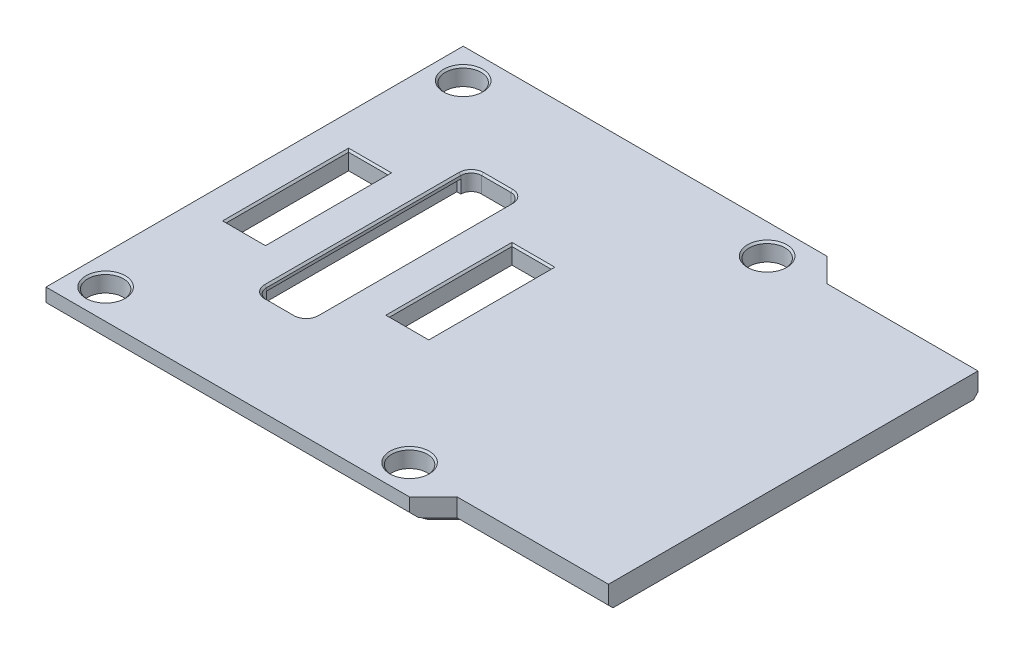
SolidWorks part; units mm, degrees
ref_plane "Front Plane" through (0, 0, 0) normal (0, 0, 1) x (1, 0, 0)
ref_plane "Top Plane" through (0, 0, 0) normal (0, 1, 0) x (1, 0, 0)
ref_plane "Right Plane" through (0, 0, 0) normal (1, 0, 0) x (0, 0, -1)
sketch "Sketch3" plane through (0, 0, 0) normal (0, 1, 0) x (1, 0, 0)
  line L0 (13.7, 0) -> (0, 0) construction
  line L1 (16.75, 10.025) -> (10.65, 10.025)
  line L2 (16.75, 10.025) -> (16.75, -10.025)
  line L3 (16.75, -10.025) -> (10.65, -10.025)
  line L4 (3.96, -16.3) -> (3.96, 16.3)
  line L5 (-2.46, -17.8) -> (2.46, -17.8)
  line L6 (-3.96, 16.3) -> (-3.96, -16.3)
  line L7 (2.46, 17.8) -> (-2.46, 17.8)
  line L8 (0, 17.8) -> (0, -17.8) construction
  line L9 (10.65, 10.025) -> (10.65, -10.025)
  line L10 (16.75, 10.025) -> (10.65, -10.025) construction
  line L11 (16.75, -10.025) -> (10.65, 10.025) construction
  line L12 (-16.75, -10.025) -> (-10.65, -10.025)
  line L13 (-16.75, 10.025) -> (-16.75, -10.025)
  line L14 (-16.75, 10.025) -> (-10.65, 10.025)
  line L15 (-10.65, 10.025) -> (-10.65, -10.025)
  arc A0 (-2.46, 17.8) -> (-3.96, 16.3) centre (-2.46, 16.3) ccw
  arc A1 (3.96, 16.3) -> (2.46, 17.8) centre (2.46, 16.3) ccw
  arc A2 (2.46, -17.8) -> (3.96, -16.3) centre (2.46, -16.3) ccw
  arc A3 (-3.96, -16.3) -> (-2.46, -17.8) centre (-2.46, -16.3) ccw
  point P9 (0, 0)
  point P23 (0, 0)
  dimension "D2" = 1.5
  dimension "D1" = 13.7
  dimension "D3" = 7.92
  dimension "D4" = 20.05
  dimension "D5" = 6.1
  dimension "D6" = 35.6
sketch "Sketch21" plane through (0, 0, 0) normal (0, 1, 0) x (1, 0, 0)
  line L1 (38.5, 35) -> (-22.5, 35)
  line L7 (38.5, 35) -> (42.5, 31)
  line L8 (-22.5, 35) -> (-22.5, -35)
  line L9 (-22.5, 0) -> (0, 0) construction
  line L10 (0, 0) -> (38.5, 0) construction
  line L11 (38.5, -35) -> (38.5, 35) construction
  line L12 (38.5, -35) -> (-22.5, -35)
  line L13 (42.5, 31) -> (67.875, 31)
  line L14 (67.875, 31) -> (67.875, -31)
  line L15 (67.875, 0) -> (38.5, 0) construction
  line L16 (42.5, -31) -> (67.875, -31)
  line L17 (38.5, -35) -> (42.5, -31)
  line L26 (16.75, 10.025) -> (10.65, 10.025)
  line L27 (10.65, 10.025) -> (10.65, -10.025)
  line L28 (10.65, -10.025) -> (16.75, -10.025)
  line L29 (16.75, -10.025) -> (16.75, 10.025)
  line L30 (16.75, 10.025) -> (10.65, 10.025) construction
  line L31 (10.65, 10.025) -> (10.65, -10.025) construction
  line L32 (10.65, -10.025) -> (16.75, -10.025) construction
  line L33 (16.75, -10.025) -> (16.75, 10.025) construction
  line L34 (-10.4, -10.275) -> (-10.4, 10.275)
  line L35 (-10.4, 10.275) -> (-17, 10.275)
  line L36 (-17, 10.275) -> (-17, -10.275)
  line L37 (-17, -10.275) -> (-10.4, -10.275)
  line L38 (-16.75, -10.025) -> (-10.65, -10.025)
  line L39 (-10.65, -10.025) -> (-10.65, 10.025)
  line L40 (-10.65, 10.025) -> (-16.75, 10.025)
  line L41 (-16.75, 10.025) -> (-16.75, -10.025)
  line L42 (-16.75, -10.025) -> (-10.65, -10.025) construction
  line L43 (-10.65, -10.025) -> (-10.65, 10.025) construction
  line L44 (-10.65, 10.025) -> (-16.75, 10.025) construction
  line L45 (-16.75, 10.025) -> (-16.75, -10.025) construction
  line L46 (-3.96, 16.3) -> (-3.96, -16.3)
  line L47 (2.46, 17.8) -> (-2.46, 17.8)
  line L48 (3.96, -16.3) -> (3.96, 16.3)
  line L49 (-2.46, -17.8) -> (2.46, -17.8)
  line L50 (-3.96, 16.3) -> (-3.96, -16.3) construction
  line L51 (2.46, 17.8) -> (-2.46, 17.8) construction
  line L52 (3.96, -16.3) -> (3.96, 16.3) construction
  line L53 (-2.46, -17.8) -> (2.46, -17.8) construction
  line L54 (-4.21, 16.3) -> (-4.21, -16.3)
  line L55 (-2.46, -18.05) -> (2.46, -18.05)
  line L56 (4.21, -16.3) -> (4.21, 16.3)
  line L57 (2.46, 18.05) -> (-2.46, 18.05)
  line L58 (17, 10.275) -> (10.4, 10.275)
  line L59 (10.4, 10.275) -> (10.4, -10.275)
  line L60 (10.4, -10.275) -> (17, -10.275)
  line L61 (17, -10.275) -> (17, 10.275)
  circle A4 centre (-17.5, 30) radius 1.6 construction
  circle A5 centre (33.5, 30) radius 1.6 construction
  circle A6 centre (33.5, -30) radius 1.6 construction
  circle A7 centre (-17.5, -30) radius 1.6 construction
  circle A8 centre (-17.5, 30) radius 3
  circle A9 centre (-17.5, -30) radius 3
  circle A10 centre (33.5, -30) radius 3
  circle A11 centre (33.5, 30) radius 3
  arc A12 (-4.21, -16.3) -> (-2.46, -18.05) centre (-2.46, -16.3) ccw
  arc A13 (2.46, -18.05) -> (4.21, -16.3) centre (2.46, -16.3) ccw
  arc A14 (4.21, 16.3) -> (2.46, 18.05) centre (2.46, 16.3) ccw
  arc A15 (-2.46, 18.05) -> (-4.21, 16.3) centre (-2.46, 16.3) ccw
  arc A16 (-2.46, 17.8) -> (-3.96, 16.3) centre (-2.46, 16.3) ccw
  arc A17 (3.96, 16.3) -> (2.46, 17.8) centre (2.46, 16.3) ccw
  arc A18 (2.46, -17.8) -> (3.96, -16.3) centre (2.46, -16.3) ccw
  arc A19 (-3.96, -16.3) -> (-2.46, -17.8) centre (-2.46, -16.3) ccw
  arc A20 (-2.46, 17.8) -> (-3.96, 16.3) centre (-2.46, 16.3) ccw construction
  arc A21 (3.96, 16.3) -> (2.46, 17.8) centre (2.46, 16.3) ccw construction
  arc A22 (2.46, -17.8) -> (3.96, -16.3) centre (2.46, -16.3) ccw construction
  arc A23 (-3.96, -16.3) -> (-2.46, -17.8) centre (-2.46, -16.3) ccw construction
  dimension "D16" = 3.2
  dimension "D2" = 6
  dimension "D3" = 0
  dimension "D4" = 0
  dimension "D5" = 0
  dimension "D6" = 0.25
  dimension "D9" = 22.5
  dimension "D10" = 61
  dimension "D11" = 35
  dimension "D12" = 5
  dimension "D13" = 5
  dimension "D14" = 5
  dimension "D15" = 5
  dimension "D17" = 45
  dimension "D18" = 4
  dimension "D19" = 25.375
extrude "Boss-Extrude3" add sketch "Sketch21" along normal blind 3
sketch "Sketch28" plane through (0, 0, 0) normal (0, -1, 0) x (1, 0, 0)
  line L9 (42.5, -31) -> (67.875, -31) construction
  line L13 (39.5, 34) -> (39.5, -34)
  line L14 (38.5, 35) -> (39.5, 34) construction
  line L17 (67.875, -31) -> (67.875, 31) construction
  line L18 (42.5, 31) -> (67.875, 31) construction
  line L19 (38.5, 35) -> (38.5, -35) construction
  line L20 (42.5, -31) -> (67.875, -31)
  line L21 (67.875, -31) -> (67.875, 31)
  line L22 (42.5, 31) -> (67.875, 31)
  line L23 (38.5, 35) -> (38.5, -35) construction
  line L24 (38.5, -35) -> (42.5, -31) construction
  line L25 (39.5, -34) -> (42.5, -31)
  line L26 (38.5, 35) -> (42.5, 31) construction
  line L27 (39.5, 34) -> (42.5, 31)
  line L28 (38.5, -35) -> (39.5, -34) construction
  dimension "D1" = 1
extrude "Boss-Extrude2" add sketch "Sketch28" along normal blind 0.8
sketch "Sketch29" plane through (0, 0, 0) normal (0, -1, 0) x (1, 0, 0)
  line L0 (-4.21, 16.3) -> (-4.875, 16.3)
  line L1 (-4.875, 16.3) -> (-4.875, -16.3)
  line L2 (-4.875, -16.3) -> (-4.21, -16.3)
  line L3 (-4.21, -16.3) -> (4.21, -16.3)
  line L4 (4.21, -16.3) -> (4.875, -16.3)
  line L5 (4.875, -16.3) -> (4.875, 16.3)
  line L6 (4.875, 16.3) -> (4.21, 16.3)
  line L7 (4.21, 16.3) -> (-4.21, 16.3)
  line L8 (0, 16.3) -> (0, 0) construction
  line L9 (0, 0) -> (4.875, 0) construction
  line L10 (0, 0) -> (-4.875, 0) construction
  arc A0 (-4.21, -16.3) -> (-2.46, -18.05) centre (-2.46, -16.3) ccw construction
  dimension "D1" = 9.75
extrude "Cut-Extrude1" cut sketch "Sketch29" against normal blind 2.2
sketch "Sketch30" plane through (0, 0, 0) normal (0, -1, 0) x (1, 0, 0)
  line L0 (30, -14.5) -> (30, 35) construction
  line L2 (-22.5, 35) -> (38.5, 35) construction
  text T0 "Ms6p" font "Microsoft Sans Serif" height 8
  dimension "D1" = 30
  dimension "D2" = 14.5
extrude "Cut-Extrude2" cut sketch "Sketch30" against normal blind 1
chamfer "Chamfer1" distance 0.3 angle 45 20 edges at (33.5, 3, 33) (-17.5, 3, 33) (-17.5, 3, -27) (33.5, 3, -27) (17, 3, 0) (13.7, 3, -10.275) (10.4, 3, 0) (13.7, 3, 10.275) (-13.7, 3, 10.275) (-17, 3, 0) (-10.4, 3, 0) (-13.7, 3, -10.275) (0, 3, 18.05) (3.6974, 3, 17.5374) (-3.6974, 3, 17.5374) (4.21, 3, 0) (-4.21, 3, 0) (3.6974, 3, -17.5374) (-3.6974, 3, -17.5374) (0, 3, -18.05)
chamfer "Chamfer2" distance 0.75 angle 45 7 edges at (41, -0.8, 32.5) (55.1875, -0.8, 31) (55.1875, -0.8, -31) (41, -0.8, -32.5) (8, 0, -35) (8, 0, 35) (-22.5, 0, 0)
